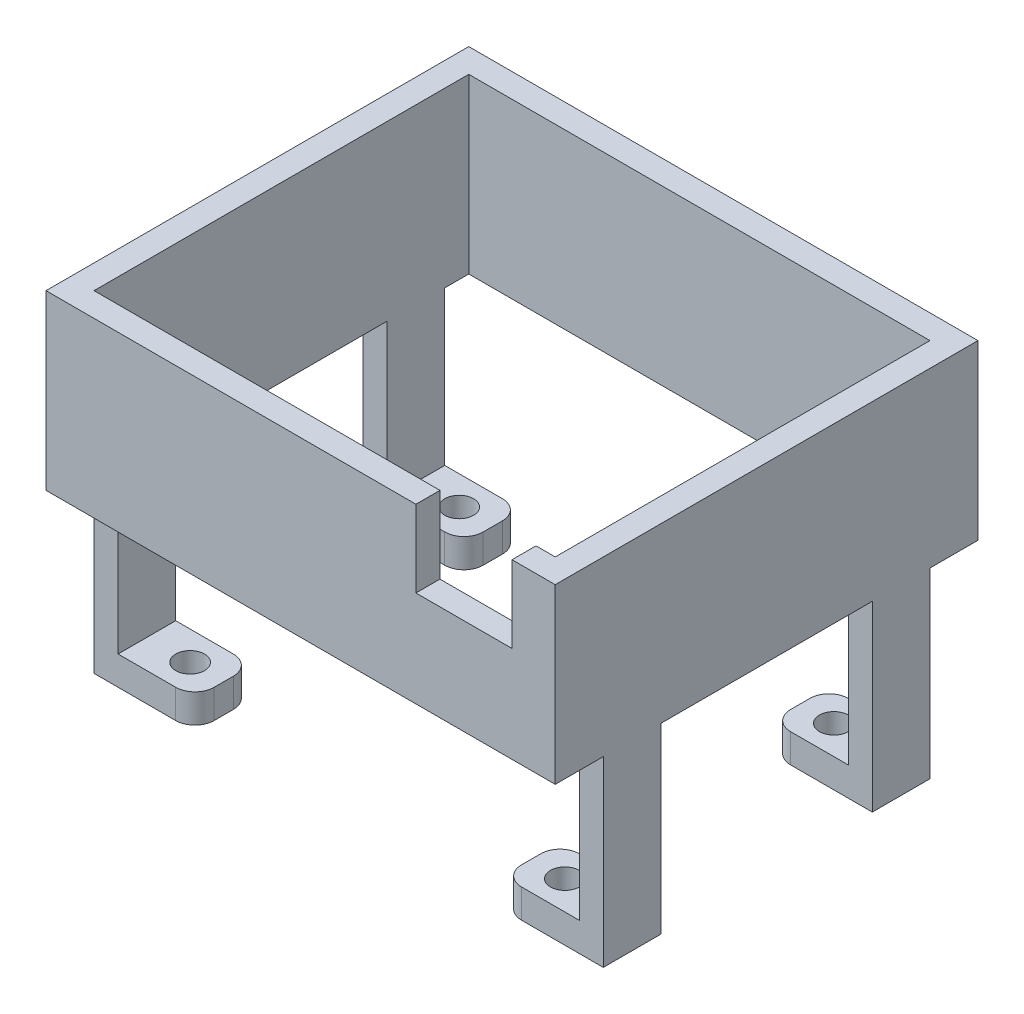
SolidWorks part; units mm, degrees
material "聚脂树脂"
ref_plane "前视基准面" through (0, 0, 0) normal (0, 0, 1) x (1, 0, 0)
ref_plane "上视基准面" through (0, 0, 0) normal (0, 1, 0) x (1, 0, 0)
ref_plane "右视基准面" through (0, 0, 0) normal (1, 0, 0) x (0, 0, -1)
other "Configuration Table"
sketch "草图1" plane through (0, 0, 0) normal (0, 1, 0) x (1, 0, 0)
  line L1 (-24, -19.5) -> (24, -19.5)
  line L2 (-24, -19.5) -> (-24, 19.5)
  line L3 (-24, 19.5) -> (24, 19.5)
  line L4 (24, -19.5) -> (24, 19.5)
  line L5 (-24, -19.5) -> (24, 19.5) construction
  line L6 (-24, 19.5) -> (24, -19.5) construction
  line L7 (-26.5, -22) -> (26.5, -22)
  line L8 (-26.5, -22) -> (-26.5, 22)
  line L9 (-26.5, 22) -> (26.5, 22)
  line L10 (26.5, -22) -> (26.5, 22)
  line L11 (-26.5, -22) -> (26.5, 22) construction
  line L12 (-26.5, 22) -> (26.5, -22) construction
  point P0 (0, 0)
  point P6 (0, 0)
  dimension "D1" = 48
  dimension "D2" = 53
  dimension "D3" = 39
  dimension "D4" = 44
extrude "凸台-拉伸1" add sketch "草图1" along normal blind 18
sketch "草图2" plane through (0, 0, 0) normal (0, -1, 0) x (1, 0, 0)
  line L0 (0, 0) -> (0, 28.405) construction
  line L1 (0, 0) -> (40.0793, 0) construction
  line L2 (24, 11) -> (24, 17)
  line L3 (24, 19.5) -> (24, -19.5) construction
  line L4 (24, 17) -> (26.5, 17)
  line L5 (26.5, 22) -> (26.5, -22) construction
  line L6 (26.5, 17) -> (26.5, 11)
  line L7 (26.5, 11) -> (24, 11)
  line L8 (26.5, -17) -> (26.5, -11)
  line L9 (24, -17) -> (26.5, -17)
  line L10 (24, -11) -> (24, -17)
  line L11 (26.5, -11) -> (24, -11)
  line L12 (-26.5, -11) -> (-24, -11)
  line L13 (-24, -11) -> (-24, -17)
  line L14 (-24, -17) -> (-26.5, -17)
  line L15 (-26.5, -17) -> (-26.5, -11)
  line L16 (-26.5, 11) -> (-24, 11)
  line L17 (-26.5, 17) -> (-26.5, 11)
  line L18 (-24, 17) -> (-26.5, 17)
  line L19 (-24, 11) -> (-24, 17)
  dimension "D1" = 6
  dimension "D2" = 11
extrude "凸台-拉伸2" add sketch "草图2" along normal blind 16
sketch "草图3" plane through (0, -16, 0) normal (0, -1, 0) x (1, 0, 0)
  line L0 (0, 0) -> (0, 31.4328) construction
  line L1 (0, 0) -> (49.8837, 0) construction
  line L2 (24, 17) -> (26.5, 17)
  line L3 (26.5, 11) -> (26.5, 17) construction
  line L4 (26.5, 17) -> (24, 17) construction
  line L5 (26.5, 17) -> (26.5, 11)
  line L6 (26.5, 11) -> (24, 11)
  line L7 (24, 11) -> (24, 17)
  line L8 (24, 17) -> (16, 17)
  line L9 (16, 17) -> (16, 11)
  line L10 (16, 11) -> (24, 11)
  line L11 (16, -11) -> (24, -11)
  line L12 (16, -17) -> (16, -11)
  line L13 (24, -17) -> (16, -17)
  line L14 (24, -11) -> (24, -17)
  line L15 (26.5, -11) -> (24, -11)
  line L16 (26.5, -17) -> (26.5, -11)
  line L17 (24, -17) -> (26.5, -17)
  line L18 (-24, -17) -> (-26.5, -17)
  line L19 (-26.5, -17) -> (-26.5, -11)
  line L20 (-26.5, -11) -> (-24, -11)
  line L21 (-24, -11) -> (-24, -17)
  line L22 (-24, -17) -> (-16, -17)
  line L23 (-16, -17) -> (-16, -11)
  line L24 (-16, -11) -> (-24, -11)
  line L25 (-16, 11) -> (-24, 11)
  line L26 (-16, 17) -> (-16, 11)
  line L27 (-24, 17) -> (-16, 17)
  line L28 (-24, 11) -> (-24, 17)
  line L29 (-26.5, 11) -> (-24, 11)
  line L30 (-26.5, 17) -> (-26.5, 11)
  line L31 (-24, 17) -> (-26.5, 17)
  circle A0 centre (19.5, 14) radius 1.5
  circle A1 centre (19.5, -14) radius 1.5
  circle A2 centre (-19.5, -14) radius 1.5
  circle A3 centre (-19.5, 14) radius 1.5
  line M4 (24, 11) -> (26.5, 11)
  line M5 (26.5, 11) -> (26.5, 17)
  line M6 (26.5, 17) -> (24, 17)
  line M7 (24, 17) -> (24, 11)
  dimension "D1" = 3
  dimension "D2" = 28
  dimension "D4" = 39
  dimension "D3" = 8
extrude "凸台-拉伸3" add sketch "草图3" along normal blind 3 contours L28 L25 L26 L27 A3 | L28 L31 L30 L29 | M7 M4 M5 M6 | L9 L10 L8 A0 M7 | L14 L11 L12 L13 A1 | L14 L17 L16 L15 | L21 L20 L19 L18 | L23 L24 L21 L22 A2
fillet "圆角1" radius 2 8 edges at (16, -17.5, -17) (16, -17.5, -11) (16, -17.5, 17) (16, -17.5, 11) (-16, -17.5, 17) (-16, -17.5, 11) (-16, -17.5, -11) (-16, -17.5, -17)
sketch "草图4" plane through (0, 0, 22) normal (0, 0, 1) x (1, 0, 0)
  line L0 (12, 18) -> (12, 10)
  line L2 (12, 10) -> (22, 10)
  line L3 (22, 10) -> (22, 18)
  line L4 (22, 18) -> (12, 18)
  line L5 (0, 0) -> (0, 14.7426) construction
  line L6 (0, 0) -> (29.6996, 0) construction
  line L7 (-26.5, 18) -> (26.5, 18) construction
  dimension "D1" = 10
  dimension "D2" = 8
  dimension "D3" = 12
  dimension "D4" = 0
extrude "切除-拉伸1" cut sketch "草图4" against normal blind 5
